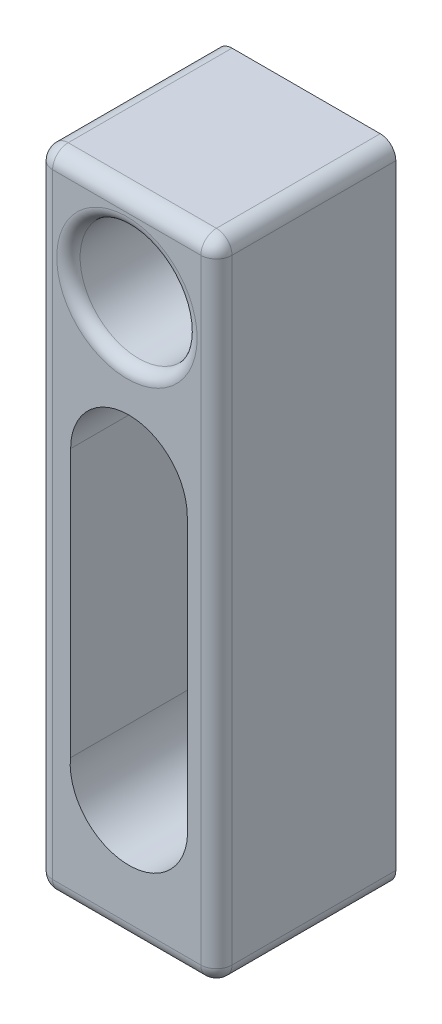
SolidWorks part; units mm, degrees
ref_plane "Front Plane" through (0, 0, 0) normal (0, 0, 1) x (1, 0, 0)
ref_plane "Top Plane" through (0, 0, 0) normal (0, 1, 0) x (1, 0, 0)
ref_plane "Right Plane" through (0, 0, 0) normal (1, 0, 0) x (0, 0, -1)
sketch "Sketch1" plane through (0, 0, 0) normal (0, 0, 1) x (1, 0, 0)
  line L0 (0, 0) -> (0, -8.28)
  line L1 (0, -8.28) -> (2.3, -8.28)
  line L2 (2.3, -8.28) -> (2.3, 0)
  line L3 (2.3, 0) -> (0, 0)
  dimension "D1" = 8.28
  dimension "D2" = 2.3
extrude "Boss-Extrude1" add sketch "Sketch1" along normal blind 2.3 contours L1 L2 L3 L0
sketch "Sketch4" plane through (-0.0476, -0.2311, 2.3) normal (0, 0, 1) x (1, 0, 0)
  circle A2 centre (1.2006, -0.9136) radius 0.75
  point P2 (0, 0)
extrude "Cut-Extrude3" cut sketch "Sketch4" against normal blind 2.6274 contours A2
fillet "Fillet7" radius 0.2 1 edges at (1.15, 0, 2.3)
fillet "Fillet8" radius 0.2 3 edges at (2.3, 0, 1.05) (2.3, -0.0586, 2.2414) (2.3, -4.24, 2.3)
fillet "Fillet9" radius 0.2 3 edges at (0, 0, 1.05) (0, -0.0586, 2.2414) (0, -4.24, 2.3)
fillet "Fillet10" radius 0.2 5 edges at (0, -8.28, 1.05) (0.0586, -8.28, 2.2414) (2.3, -8.28, 1.05) (2.2414, -8.28, 2.2414) (1.15, -8.28, 2.3)
fillet "Fillet12" radius 0.15 1 edges at (1.903, -1.1447, 2.3)
fillet "Fillet13" radius 0.15 1 edges at (1.903, -1.1447, 0)
sketch "Sketch9" plane through (0, -0.2203, 2.3) normal (0, 0, 1) x (1, 0, 0)
  line L4 (0.428, -2.9605) -> (0.428, -6.4605)
  line L10 (1.928, -2.9605) -> (1.928, -6.4605)
  line L11 (1.928, -6.4605) -> (0.428, -6.4605)
  line L12 (0.428, -2.9605) -> (1.928, -2.9605)
  line L13 (0.4275, -2.9809) -> (0.4275, -6.4809)
  circle A2 centre (1.178, -2.9605) radius 0.747
  circle A3 centre (1.178, -6.4605) radius 0.7529
extrude "Cut-Extrude4" cut sketch "Sketch9" against normal blind 2.3
